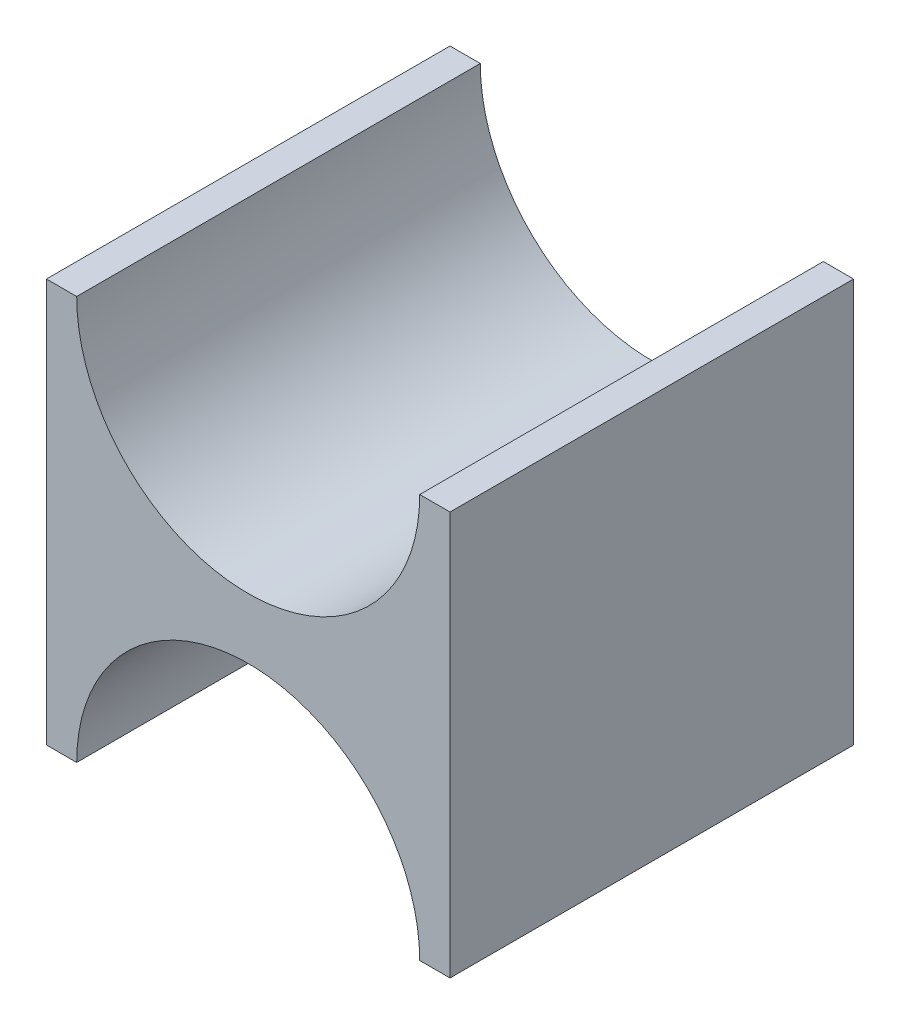
SolidWorks part; units mm, degrees
ref_plane "Front Plane" through (0, 0, 0) normal (0, 0, 1) x (1, 0, 0)
ref_plane "Top Plane" through (0, 0, 0) normal (0, 1, 0) x (1, 0, 0)
ref_plane "Right Plane" through (0, 0, 0) normal (1, 0, 0) x (0, 0, -1)
sketch "Sketch1" plane through (0, 0, 0) normal (0, 0, 1) x (1, 0, 0)
  line L0 (-10, -10) -> (-8.5, -10)
  line L1 (10, -10) -> (8.5, -10)
  line L2 (10, 10) -> (10, -10)
  line L3 (8.5, 10) -> (10, 10)
  line L4 (-10, 10) -> (-10, -10)
  line L7 (-8.5, 10) -> (-10, 10)
  arc A0 (-8.5, -10) -> (8.5, -10) centre (0, -10) cw
  arc A1 (8.5, 10) -> (-8.5, 10) centre (0, 10) cw
  point P0 (0, 0)
extrude "Boss-Extrude1" add sketch "Sketch1" along normal blind 20
